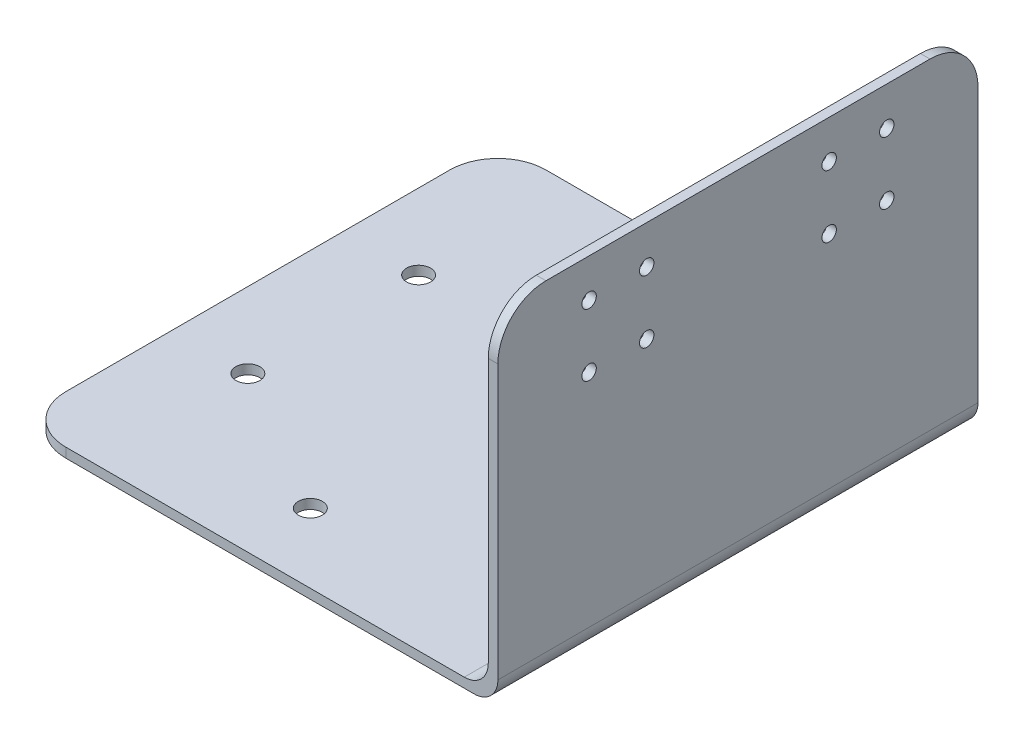
SolidWorks part; units mm, degrees
ref_plane "前视基准面" through (0, 0, 0) normal (0, 0, 1) x (1, 0, 0)
ref_plane "上视基准面" through (0, 0, 0) normal (0, 1, 0) x (1, 0, 0)
ref_plane "右视基准面" through (0, 0, 0) normal (1, 0, 0) x (0, 0, -1)
sketch "Sketch1" plane through (0, 0, 0) normal (0, 0, 1) x (1, 0, 0)
  line L1 (-1, 25) -> (1, 25)
  line L2 (-1, 25) -> (-1, -40)
  line L4 (1, 25) -> (1, -42)
  line L7 (-6, -45) -> (-99, -45)
  line L9 (-4, -47) -> (-99, -47)
  line L10 (-99, -45) -> (-99, -47)
  arc A0 (-4, -47) -> (1, -42) centre (-4, -42) ccw
  arc A1 (-1, -40) -> (-6, -45) centre (-6, -40) cw
  point P0 (0, 0)
  point P15 (1, -47)
  point P18 (-1, -45)
  dimension "D7" = 5
  dimension "D1" = 2
  dimension "D2" = 70
  dimension "D3" = 2
  dimension "D4" = 100
  dimension "D5" = 1
  dimension "D6" = 25
extrude "Boss-Extrude1" add sketch "Sketch1" along normal blind 100
sketch "Sketch2" plane through (-1, 0, 0) normal (-1, 0, 0) x (0, 0, 1)
  line L1 (50, 25) -> (50, -12.9) construction
  line L5 (100, 25) -> (0, 25) construction
  circle A1 centre (19, 4) radius 1.5
  circle A9 centre (31, 4) radius 1.5
  circle A14 centre (31, 17) radius 1.5
  circle A15 centre (19, 17) radius 1.5
  circle A16 centre (81, 17) radius 1.5
  circle A17 centre (69, 17) radius 1.5
  circle A18 centre (69, 4) radius 1.5
  circle A19 centre (81, 4) radius 1.5
  dimension "D1" = 19
  dimension "D2" = 12
  dimension "D4" = 3
  dimension "D5" = 3
  dimension "D3" = 8
  dimension "D6" = 12
  dimension "D7" = 13
extrude "Cut-Extrude1" cut sketch "Sketch2" against normal through all
sketch "Sketch3" plane through (0, -45, 0) normal (0, 1, 0) x (1, 0, 0)
  line L0 (-52.5, 0) -> (-52.5, -100) construction
  line L3 (-6, 0) -> (-99, 0) construction
  line L6 (-6, -100) -> (-99, -100) construction
  line L7 (-99, -50) -> (-6, -50) construction
  line L8 (-99, -100) -> (-99, 0) construction
  line L9 (-6, -100) -> (-6, 0) construction
  circle A5 centre (-21.7041, -32.22) radius 2.5
  circle A6 centre (-52.5, -50) radius 35.56 construction
  circle A7 centre (-21.7041, -67.78) radius 2.5
  circle A8 centre (-52.5, -85.56) radius 2.5
  circle A9 centre (-83.2959, -67.78) radius 2.5
  circle A10 centre (-83.2959, -32.22) radius 2.5
  circle A11 centre (-52.5, -14.44) radius 2.5
  point P29 (-52.5, -50)
  dimension "D1" = 5
  dimension "D2" = 6
extrude "Cut-Extrude2" cut sketch "Sketch3" against normal through all
fillet "Fillet1" radius 10 4 edges at (-99, -46, 0) (-99, -46, 100) (0, 25, 0) (0, 25, 100)
